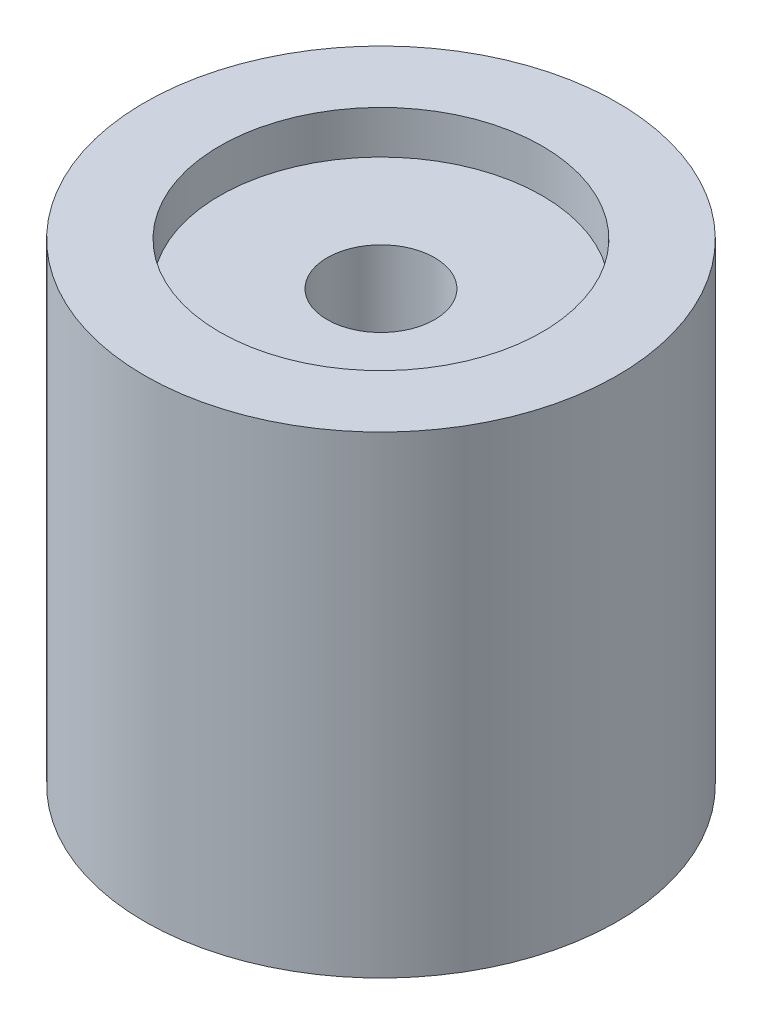
SolidWorks part; units mm, degrees
ref_plane "Front Plane" through (0, 0, 0) normal (0, 0, 1) x (1, 0, 0)
ref_plane "Top Plane" through (0, 0, 0) normal (0, 1, 0) x (1, 0, 0)
ref_plane "Right Plane" through (0, 0, 0) normal (1, 0, 0) x (0, 0, -1)
sketch "Sketch1" plane through (0, 0, 0) normal (0, 1, 0) x (1, 0, 0)
  circle A0 centre (0, 0) radius 22
  circle A1 centre (0, 0) radius 5
  dimension "D1" = 10
  dimension "D2" = 44
extrude "Boss-Extrude1" add sketch "Sketch1" along normal blind 44
sketch "Sketch2" plane through (0, 44, 0) normal (0, 1, 0) x (1, 0, 0)
  circle A0 centre (0, 0) radius 15
extrude "Cut-Extrude1" cut sketch "Sketch2" against normal blind 4
sketch "Sketch3" plane through (0, 0, 0) normal (0, -1, 0) x (1, 0, 0)
  circle A0 centre (0, 0) radius 15
extrude "Cut-Extrude2" cut sketch "Sketch3" against normal blind 4
